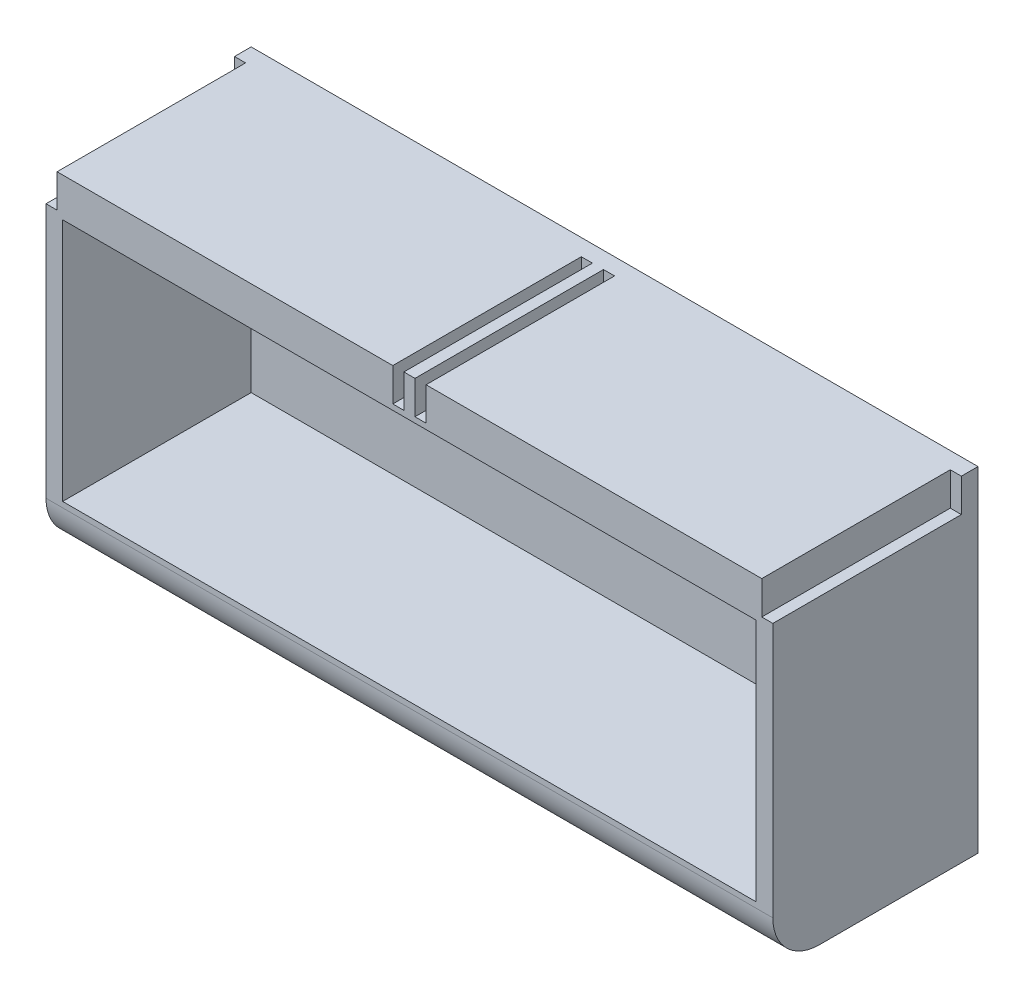
SolidWorks part; units mm, degrees
material "ABS"
ref_plane "Alzado" through (0, 0, 0) normal (0, 0, 1) x (1, 0, 0)
ref_plane "Planta" through (0, 0, 0) normal (0, 1, 0) x (1, 0, 0)
ref_plane "Vista lateral" through (0, 0, 0) normal (1, 0, 0) x (0, 0, -1)
sketch "Croquis2" plane through (0, 0, 0) normal (0, 0, 1) x (1, 0, 0)
  line L0 (0, 0) -> (131.1, 0)
  line L1 (131.1, 0) -> (131.1, -54)
  line L2 (131.1, -54) -> (0, -54)
  line L3 (0, -54) -> (0, 0)
  dimension "D1" = 131.1
  dimension "D2" = 54
extrude "Saliente-Extruir2" add sketch "Croquis2" along normal blind 3
sketch "Croquis3" plane through (0, 0, 3) normal (0, 0, 1) x (1, 0, 0)
  line L0 (0, -6) -> (2, -6)
  line L1 (0, 0) -> (0, -54) construction
  line L2 (2, -6) -> (2, 0)
  line L3 (131.1, 0) -> (0, 0) construction
  line L4 (2, 0) -> (129.1, 0)
  line L5 (129.1, 0) -> (129.1, -6)
  line L6 (129.1, -6) -> (131.1, -6)
  line L7 (131.1, -54) -> (131.1, 0) construction
  line L8 (131.1, -6) -> (131.1, -54)
  line L9 (131.1, -54) -> (0, -54)
  line L10 (0, -54) -> (0, -6)
  line L11 (65.55, 0) -> (66.55, 0)
  line L12 (65.55, 0) -> (64.55, 0)
  line L13 (64.55, 0) -> (64.55, -6)
  line L14 (66.55, 0) -> (66.55, -6)
  line L15 (64.55, -6) -> (62.55, -6)
  line L16 (62.55, -6) -> (62.55, 0)
  line L17 (66.55, -6) -> (68.55, -6)
  line L18 (68.55, -6) -> (68.55, 0)
  line L19 (3, -7) -> (128.1, -7)
  line L20 (128.1, -7) -> (128.1, -51)
  line L21 (128.1, -51) -> (3, -51)
  line L22 (3, -51) -> (3, -7)
  point P29 (129.1, -8.3236)
  point P30 (129.1, -7)
  point P31 (130.1, -6)
  line M15 (0, 0) -> (0, -54)
  line M16 (0, -54) -> (131.1, -54)
  line M17 (131.1, -54) -> (131.1, 0)
  line M18 (131.1, 0) -> (0, 0)
  dimension "D1" = 2
  dimension "D2" = 2
  dimension "D3" = 6
  dimension "D4" = 2
  dimension "D5" = 2
  dimension "D6" = 1
  dimension "D7" = 1
  dimension "D8" = 3
  dimension "D9" = 3
  dimension "D10" = 3
  dimension "D11" = 1
extrude "Saliente-Extruir3" add sketch "Croquis3" along normal blind 34 contours L18 L17 L14 L4 L13 L15 L16 L2 L0 L6 L5 L21 L22 L19 L20 M18 M15 M16 M17
sketch "Croquis4" plane through (0, -54, 0) normal (0, -1, 0) x (1, 0, 0)
  line L4 (0, 0) -> (131.1, 0)
  line L5 (131.1, 0) -> (131.1, 37)
  line L6 (131.1, 37) -> (0, 37)
  line L7 (0, 37) -> (0, 0)
  line L8 (0, 0) -> (131.1, 0)
  line L9 (131.1, 0) -> (131.1, 37)
  line L10 (131.1, 37) -> (0, 37)
  line L11 (0, 37) -> (0, 0)
  dimension "D1" = 0
extrude "Saliente-Extruir4" add sketch "Croquis4" along normal blind 6.4
fillet "Redondeo2" radius 8.4 1 edges at (65.55, -60.4, 37)
